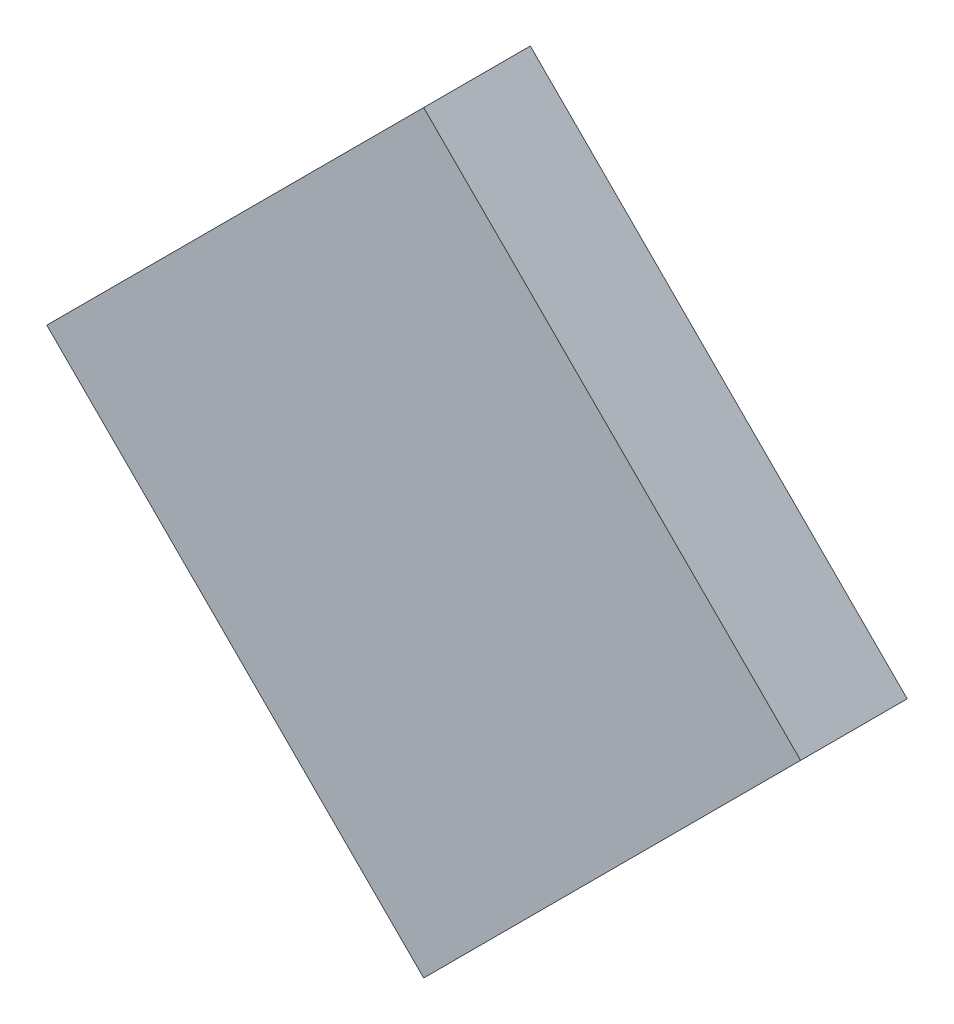
SolidWorks part; units mm, degrees
material "NdFeB"
ref_plane "Ön Düzlem" through (0, 0, 0) normal (0, 0, 1) x (1, 0, 0)
ref_plane "Üst Düzlem" through (0, 0, 0) normal (0, 1, 0) x (1, 0, 0)
ref_plane "Sağ Düzlem" through (0, 0, 0) normal (1, 0, 0) x (0, 0, -1)
sketch "Sketch1" plane through (0, 0, 0) normal (0, 0, 1) x (1, 0, 0)
  line L0 (-42.4264, 0) -> (0, -42.4264)
  line L5 (-42.4264, 0) -> (0, 42.4264)
  line L6 (0, -42.4264) -> (42.4264, 0)
  line L11 (0, 42.4264) -> (42.4264, 0)
  dimension "m1" = 60
extrude "Boss-Extrude1" add sketch "Sketch1" along normal blind 12
